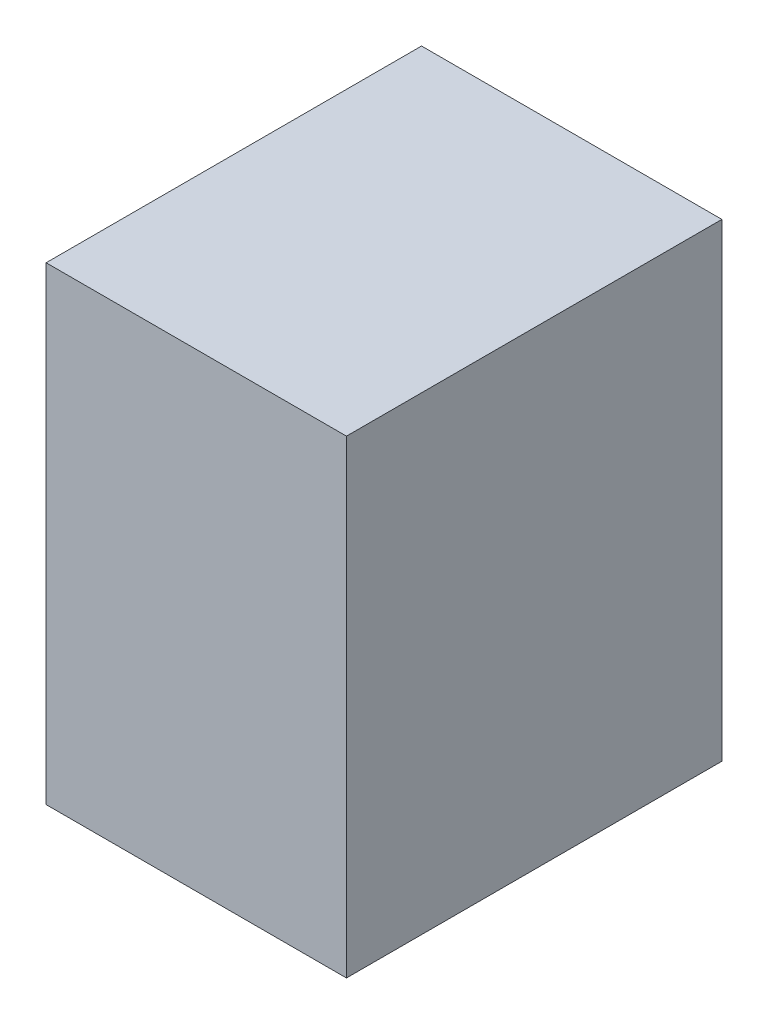
SolidWorks part; units mm, degrees
ref_plane "Front Plane" through (0, 0, 0) normal (0, 0, 1) x (1, 0, 0)
ref_plane "Top Plane" through (0, 0, 0) normal (0, 1, 0) x (1, 0, 0)
ref_plane "Right Plane" through (0, 0, 0) normal (1, 0, 0) x (0, 0, -1)
sketch "Sketch1" plane through (0, 0, 0) normal (0, 0, 1) x (1, 0, 0)
  line L1 (-16, 25) -> (16, 25)
  line L2 (-16, 25) -> (-16, -25)
  line L3 (-16, -25) -> (16, -25)
  line L4 (16, 25) -> (16, -25)
  line L5 (-16, 25) -> (16, -25) construction
  line L6 (-16, -25) -> (16, 25) construction
  point P0 (0, 0)
  dimension "D1" = 50
  dimension "D2" = 32
extrude "Boss-Extrude1" add sketch "Sketch1" against normal blind 40
